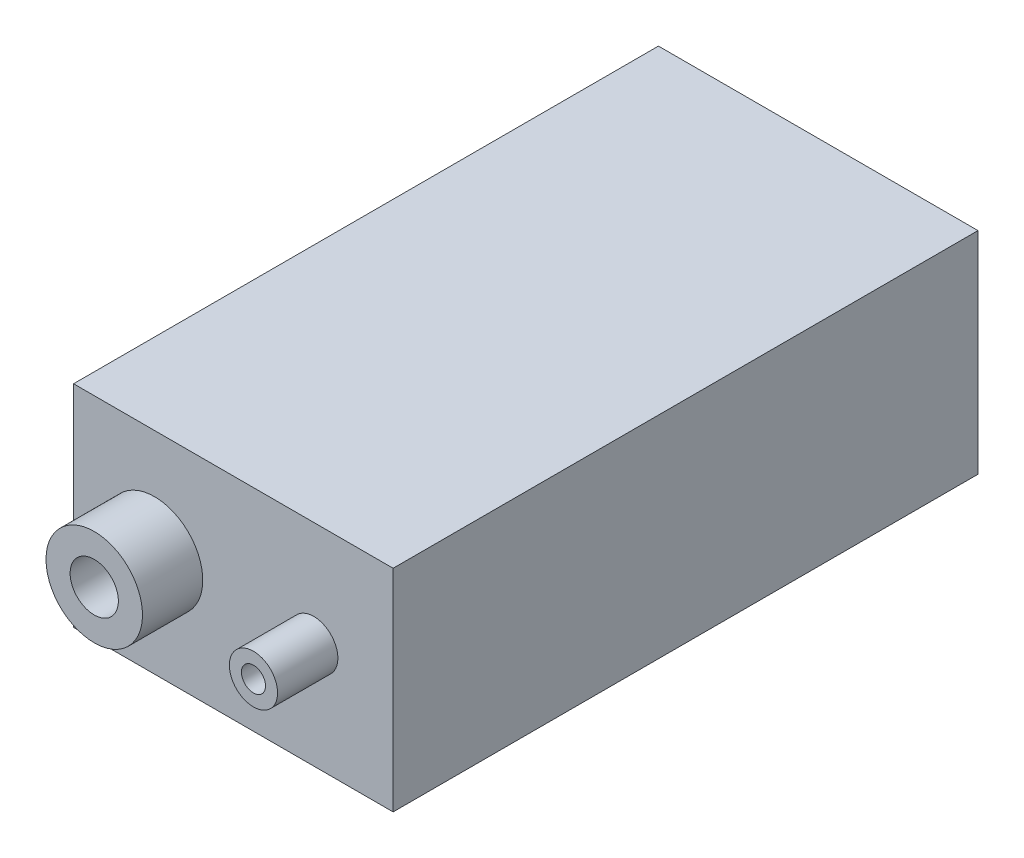
SolidWorks part; units mm, degrees
ref_plane "Front Plane" through (0, 0, 0) normal (0, 0, 1) x (1, 0, 0)
ref_plane "Top Plane" through (0, 0, 0) normal (0, 1, 0) x (1, 0, 0)
ref_plane "Right Plane" through (0, 0, 0) normal (1, 0, 0) x (0, 0, -1)
sketch "Sketch1" plane through (0, 0, 0) normal (0, 0, 1) x (1, 0, 0)
  line L1 (0, 0) -> (26.5, 0)
  line L2 (0, 0) -> (0, 17.5)
  line L3 (0, 17.5) -> (26.5, 17.5)
  line L4 (26.5, 0) -> (26.5, 17.5)
  dimension "D1" = 26.5
  dimension "D2" = 17.5
extrude "Boss-Extrude1" add sketch "Sketch1" along normal blind 48.5
sketch "Sketch2" plane through (0, 0, 48.5) normal (0, 0, 1) x (1, 0, 0)
  line L0 (0, 0) -> (26.5, 17.5) construction
  line L1 (26.5, 8.75) -> (13.25, 8.75) construction
  line L2 (26.5, 0) -> (26.5, 17.5) construction
  line L4 (13.317, 8.7942) -> (13.317, 0.2001) construction
  circle A0 centre (19.919, 8.75) radius 2
  circle A1 centre (6.7149, 8.75) radius 2
  circle A2 centre (6.7149, 8.75) radius 4
  circle A3 centre (19.919, 8.75) radius 1
  dimension "D1" = 2
  dimension "D2" = 1
extrude "Boss-Extrude2" add sketch "Sketch2" along normal blind 5
